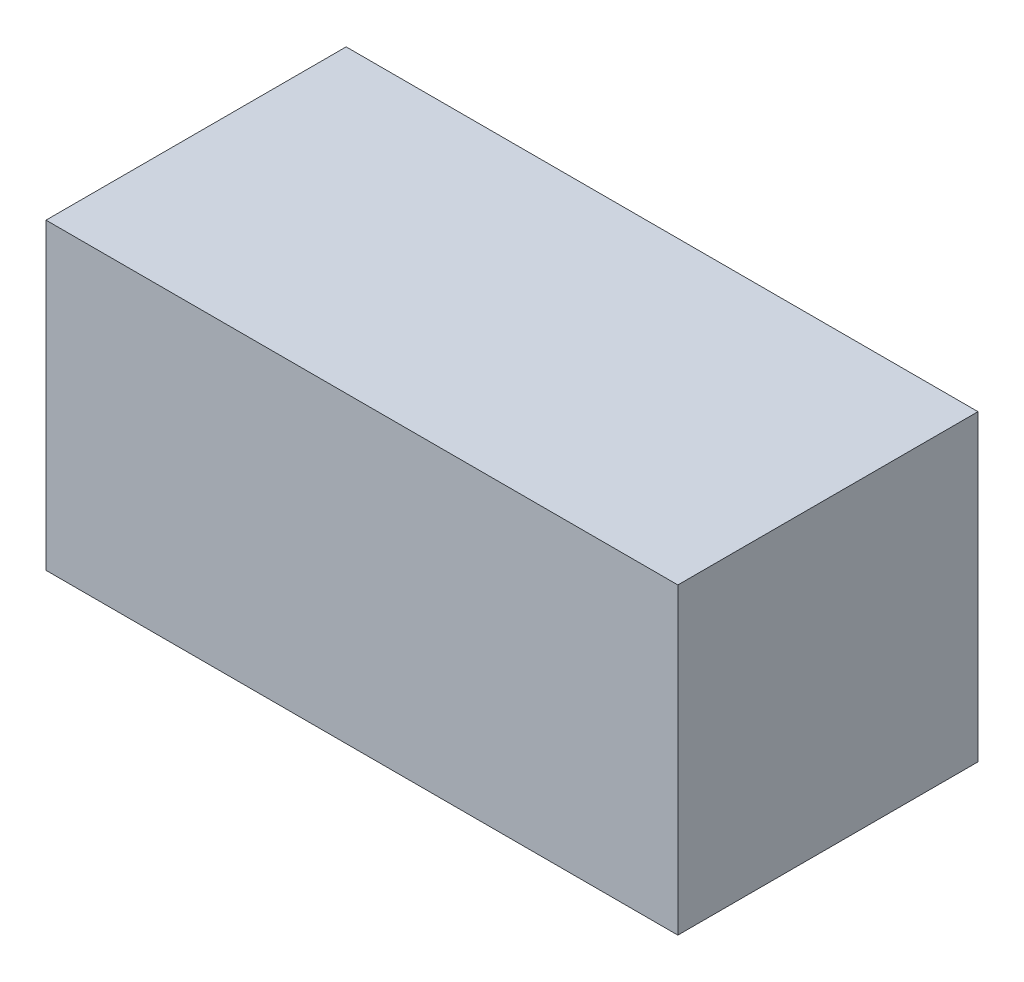
SolidWorks part; units mm, degrees
ref_plane "前视基准面" through (0, 0, 0) normal (0, 0, 1) x (1, 0, 0)
ref_plane "上视基准面" through (0, 0, 0) normal (0, 1, 0) x (1, 0, 0)
ref_plane "右视基准面" through (0, 0, 0) normal (1, 0, 0) x (0, 0, -1)
sketch "草图1" plane through (0, 0, 0) normal (0, 0, 1) x (1, 0, 0)
  line L0 (-1, -0.48) -> (1, -0.48)
  line L1 (1, -0.48) -> (1, 0.48)
  line L2 (1, 0.48) -> (-1, 0.48)
  line L3 (-1, 0.48) -> (-1, -0.48)
extrude "Component_Outline" add sketch "草图1" along normal blind 0.95 separate body
sketch3d "3D草图1"
  line L0 (0, 0, 0) -> (1, 0, 0)
  line L1 (0, 0, 0) -> (0, 1, 0)
  line L2 (0, 0, 0) -> (0, 0, 1)
  point P0 (0, 0, 0)
